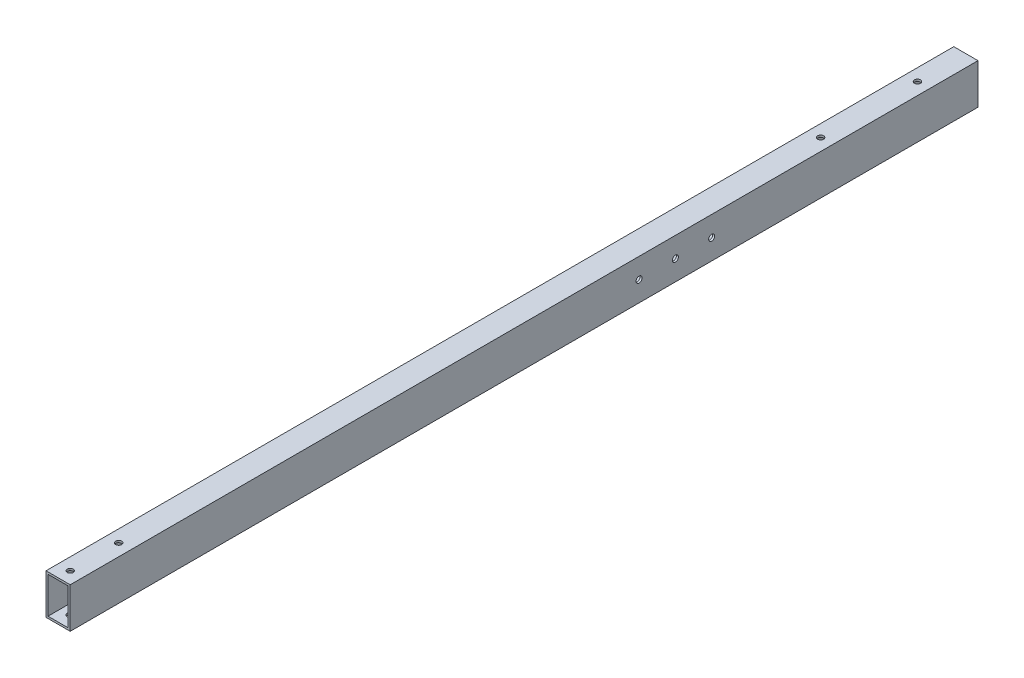
SolidWorks part; units mm, degrees
ref_plane "Front Plane" through (0, 0, 0) normal (0, 0, 1) x (1, 0, 0)
ref_plane "Top Plane" through (0, 0, 0) normal (0, 1, 0) x (1, 0, 0)
ref_plane "Right Plane" through (0, 0, 0) normal (1, 0, 0) x (0, 0, -1)
sketch "Sketch1" plane through (0, 0, 0) normal (0, 0, 1) x (1, 0, 0)
  line L0 (-5, 9) -> (5, 9)
  line L1 (-6, -10) -> (6, -10)
  line L2 (-6, -10) -> (-6, 10)
  line L3 (-6, 10) -> (6, 10)
  line L4 (6, -10) -> (6, 10)
  line L5 (-6, -10) -> (6, 10) construction
  line L6 (-6, 10) -> (6, -10) construction
  line L7 (5, -9) -> (5, 9)
  line L8 (-5, -9) -> (5, -9)
  line L9 (-5, -9) -> (-5, 9)
  point P0 (0, 0)
  dimension "D2" = 12
  dimension "D3" = 20
  dimension "D1" = 1
extrude "Boss-Extrude1" add sketch "Sketch1" along normal blind 450
sketch "Sketch2" plane through (6, 0, 0) normal (1, 0, 0) x (0, 0, -1)
  line L0 (0, 0) -> (-450, 0) construction
  line L1 (-450, -10) -> (-450, 10) construction
  line L2 (0, -10) -> (0, 10) construction
  circle A0 centre (-168, 0) radius 1.5
  circle A1 centre (-150, 0) radius 1.5
  circle A2 centre (-132, 0) radius 1.5
  dimension "D2" = 3
  dimension "D3" = 18
  dimension "D4" = 150
  dimension "D1" = 3
extrude "Cut-Extrude1" cut sketch "Sketch2" against normal up to next
sketch "Sketch3" plane through (0, 10, 0) normal (0, 1, 0) x (1, 0, 0)
  line L0 (0, 0) -> (0, -450) construction
  line L1 (6, -450) -> (-6, -450) construction
  line L2 (6, 0) -> (-6, 0) construction
  circle A0 centre (0, -444) radius 1.5
  circle A1 centre (0, -420) radius 1.5
  circle A2 centre (0, -24) radius 1.5
  circle A3 centre (0, -72) radius 1.5
  dimension "D1" = 24
  dimension "D2" = 6
  dimension "D3" = 3
  dimension "D5" = 48
  dimension "D4" = 24
extrude "Cut-Extrude2" cut sketch "Sketch3" against normal through all
